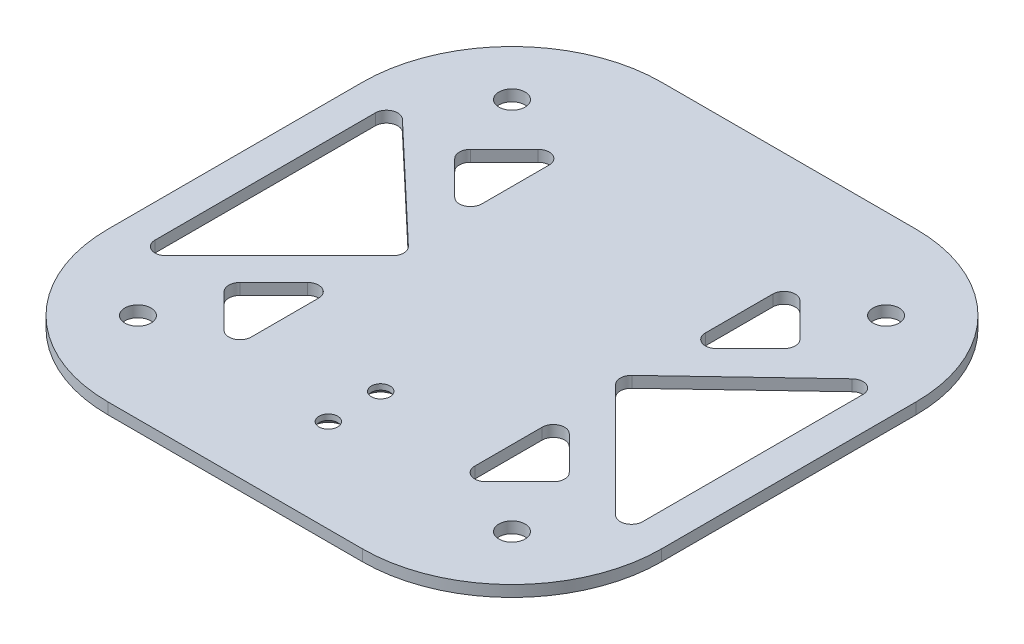
SolidWorks part; units mm, degrees
ref_plane "Front Plane" through (0, 0, 0) normal (0, 0, 1) x (1, 0, 0)
ref_plane "Top Plane" through (0, 0, 0) normal (0, 1, 0) x (1, 0, 0)
ref_plane "Right Plane" through (0, 0, 0) normal (1, 0, 0) x (0, 0, -1)
sketch "Sketch2" plane through (0, 0, 0) normal (0, 1, 0) x (1, 0, 0)
  line L0 (0, 0) -> (100, -100) construction
  line L1 (100, 0) -> (0, -100) construction
  line L2 (0, 0) -> (0, -100) construction
  line L3 (-24, -124) -> (124, -124)
  line L4 (-24, -124) -> (-24, 24)
  line L5 (-24, 24) -> (124, 24)
  line L6 (124, -124) -> (124, 24)
  line L7 (-24, -124) -> (124, 24) construction
  line L8 (-24, 24) -> (124, -124) construction
  line L9 (0, -100) -> (100, -100) construction
  line L10 (18.0626, -50) -> (77.6026, -50) construction
  line L11 (-15.1825, -21.3583) -> (-15.1825, -80.245)
  line L12 (-10.0611, -82.3663) -> (20.1839, -52.1213)
  line L13 (20.1253, -47.8217) -> (-10.1197, -19.1801)
  line L14 (50, -36.2208) -> (50, -67.8836) construction
  line L15 (110.0611, -82.3663) -> (79.8161, -52.1213)
  line L16 (115.1825, -21.3583) -> (115.1825, -80.245)
  line L17 (79.8747, -47.8217) -> (110.1197, -19.1801)
  line L18 (5.9953, -21.3014) -> (15.004, -30.3101)
  line L19 (20.1253, -28.1888) -> (20.1253, -10.1714)
  line L20 (15.004, -8.0501) -> (5.9953, -17.0587)
  line L21 (5.9953, -78.6986) -> (15.004, -69.6899)
  line L22 (20.1253, -71.8112) -> (20.1253, -89.8286)
  line L23 (15.004, -91.9499) -> (5.9953, -82.9413)
  line L24 (79.8747, -71.8112) -> (79.8747, -89.8286)
  line L25 (84.996, -91.9499) -> (94.0047, -82.9413)
  line L26 (94.0047, -78.6986) -> (84.996, -69.6899)
  line L27 (94.0047, -21.3014) -> (84.996, -30.3101)
  line L28 (84.996, -8.0501) -> (94.0047, -17.0587)
  line L29 (79.8747, -28.1888) -> (79.8747, -10.1714)
  circle A0 centre (0, 0) radius 3.5
  circle A1 centre (0, -100) radius 3.5
  circle A2 centre (100, 0) radius 3.5
  circle A3 centre (100, -100) radius 3.5
  circle A4 centre (50, -0.9046) radius 2.5
  circle A5 centre (50, -14.9046) radius 2.5
  circle A6 centre (50, -99.0954) radius 2.5
  circle A7 centre (50, -85.0954) radius 2.5
  arc A8 (-15.1825, -80.245) -> (-10.0611, -82.3663) centre (-12.1825, -80.245) ccw
  arc A9 (20.1839, -52.1213) -> (20.1253, -47.8217) centre (18.0626, -50) ccw
  arc A10 (-15.1825, -21.3583) -> (-10.1197, -19.1801) centre (-12.1825, -21.3583) cw
  arc A11 (79.8161, -52.1213) -> (79.8747, -47.8217) centre (81.9374, -50) cw
  arc A12 (115.1825, -80.245) -> (110.0611, -82.3663) centre (112.1825, -80.245) cw
  arc A13 (115.1825, -21.3583) -> (110.1197, -19.1801) centre (112.1825, -21.3583) ccw
  arc A14 (15.004, -30.3101) -> (20.1253, -28.1888) centre (17.1253, -28.1888) ccw
  arc A15 (20.1253, -10.1714) -> (15.004, -8.0501) centre (17.1253, -10.1714) ccw
  arc A16 (5.9953, -21.3014) -> (5.9953, -17.0587) centre (8.1167, -19.1801) cw
  arc A17 (15.004, -69.6899) -> (20.1253, -71.8112) centre (17.1253, -71.8112) cw
  arc A18 (20.1253, -89.8286) -> (15.004, -91.9499) centre (17.1253, -89.8286) cw
  arc A19 (5.9953, -78.6986) -> (5.9953, -82.9413) centre (8.1167, -80.8199) ccw
  arc A20 (84.996, -69.6899) -> (79.8747, -71.8112) centre (82.8747, -71.8112) ccw
  arc A21 (79.8747, -89.8286) -> (84.996, -91.9499) centre (82.8747, -89.8286) ccw
  arc A22 (94.0047, -78.6986) -> (94.0047, -82.9413) centre (91.8833, -80.8199) cw
  arc A23 (84.996, -30.3101) -> (79.8747, -28.1888) centre (82.8747, -28.1888) cw
  arc A24 (94.0047, -21.3014) -> (94.0047, -17.0587) centre (91.8833, -19.1801) ccw
  arc A25 (79.8747, -10.1714) -> (84.996, -8.0501) centre (82.8747, -10.1714) cw
  point P9 (50, -50)
  dimension "D1" = 7
  dimension "D2" = 7
  dimension "D3" = 100
  dimension "D4" = 7
  dimension "D5" = 100
  dimension "D6" = 7
  dimension "D7" = 100
  dimension "D10" = 5
  dimension "D11" = 5
  dimension "D12" = 14
  dimension "D13" = 3
  dimension "D14" = 3
  dimension "D8" = 100
  dimension "D9" = 148
extrude "Boss-Extrude1" add sketch "Sketch2" along normal blind 3
fillet "Fillet1" radius 40 4 edges at (-24, 1.5, -24) (124, 1.5, -24) (124, 1.5, 124) (-24, 1.5, 124)
chamfer "Chamfer1" distance 1.5 angle 45 4 edges at (50, 0, 17.4046) (50, 0, 96.5954) (50, 0, 82.5954) (50, 0, 3.4046)
sketch "Sketch3" plane through (0, 3, 0) normal (0, 1, 0) x (1, 0, 0)
  line L1 (38.0202, 10.9685) -> (63.2633, 10.9685)
  line L2 (38.0202, 10.9685) -> (38.0202, -27.324)
  line L3 (38.0202, -27.324) -> (63.2633, -27.324)
  line L4 (63.2633, 10.9685) -> (63.2633, -27.324)
extrude "Boss-Extrude2" add sketch "Sketch3" against normal up to surface (3 mm away) up to face at (50, 0, 10.9046)
